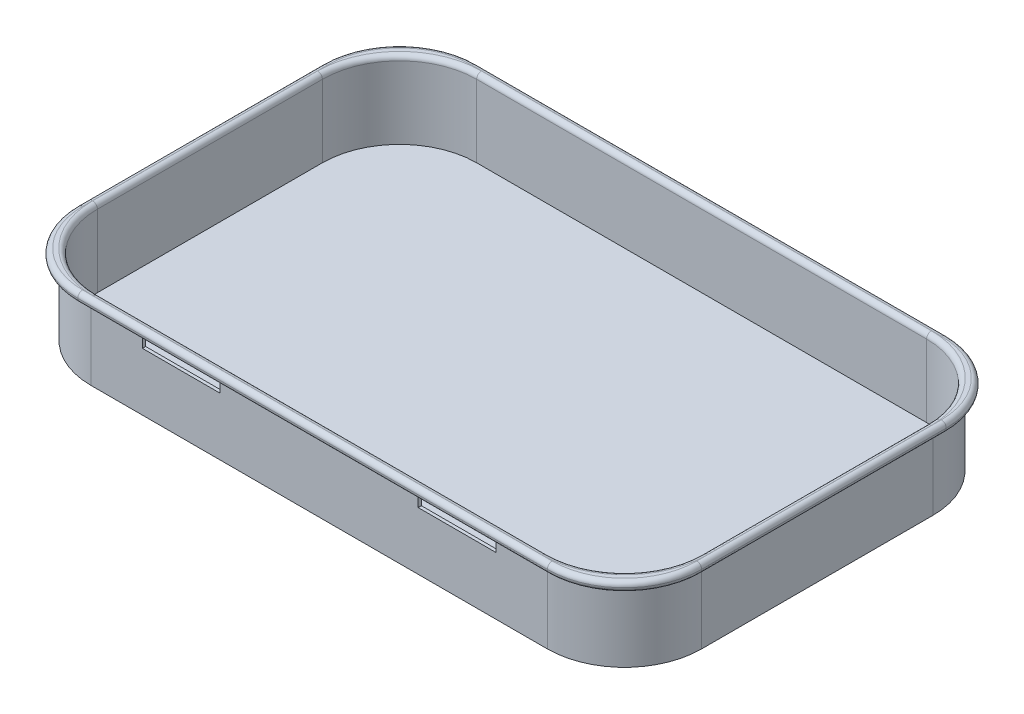
SolidWorks part; units mm, degrees
material "AISI 1010 Steel, hot rolled bar"
ref_plane "Front Plane" through (0, 0, 0) normal (0, 0, 1) x (1, 0, 0)
ref_plane "Top Plane" through (0, 0, 0) normal (0, 1, 0) x (1, 0, 0)
ref_plane "Right Plane" through (0, 0, 0) normal (1, 0, 0) x (0, 0, -1)
sketch "Sketch1" plane through (0, 0, 0) normal (0, 1, 0) x (1, 0, 0)
  line L0 (-47.5, 30) -> (47.5, -30) construction
  line L1 (-47.5, -30) -> (47.5, -30)
  line L2 (-47.5, -30) -> (-47.5, 30)
  line L3 (-47.5, 30) -> (47.5, 30)
  line L4 (47.5, -30) -> (47.5, 30)
  point P5 (0, 0)
  dimension "D1" = 95
  dimension "D2" = 60
extrude "Boss-Extrude1" add sketch "Sketch1" along normal blind 0.5
sketch "Sketch2" plane through (0, 0.5, 0) normal (0, 1, 0) x (1, 0, 0)
  line L0 (-47, -29.5) -> (47, -29.5)
  line L1 (47, -29.5) -> (47, 29.5)
  line L2 (47, 29.5) -> (-47, 29.5)
  line L3 (-47, 29.5) -> (-47, -29.5)
  line L8 (-47.5, -30) -> (47.5, -30)
  line L9 (47.5, -30) -> (47.5, 30)
  line L10 (47.5, 30) -> (-47.5, 30)
  line L11 (-47.5, 30) -> (-47.5, -30)
  line L12 (-47.5, -30) -> (47.5, -30)
  line L13 (47.5, -30) -> (47.5, 30)
  line L14 (47.5, 30) -> (-47.5, 30)
  line L15 (-47.5, 30) -> (-47.5, -30)
  line M9 (-47.5, 30) -> (-47.5, -30)
  line M10 (-47.5, -30) -> (47.5, -30)
  line M11 (47.5, -30) -> (47.5, 30)
  line M12 (47.5, 30) -> (-47.5, 30)
  dimension "D1" = 0
  dimension "D2" = 0.5
extrude "Boss-Extrude2" add sketch "Sketch2" along normal blind 10.5 contours L3 L2 L1 L0 M12 M9 M10 M11
sketch "Sketch3" plane through (0, 11, 0) normal (0, 1, 0) x (1, 0, 0)
  line L8 (-48.53, -31.03) -> (48.53, -31.03)
  line L9 (48.53, -31.03) -> (48.53, 31.03)
  line L10 (48.53, 31.03) -> (-48.53, 31.03)
  line L11 (-48.53, 31.03) -> (-48.53, -31.03)
  line L12 (-48.53, -31.03) -> (48.53, -31.03)
  line L13 (48.53, -31.03) -> (48.53, 31.03)
  line L14 (48.53, 31.03) -> (-48.53, 31.03)
  line L15 (-48.53, 31.03) -> (-48.53, -31.03)
  line L20 (47, -29.5) -> (47, 29.5)
  line L21 (-47, -29.5) -> (47, -29.5)
  line L22 (47, 29.5) -> (-47, 29.5)
  line L23 (-47, 29.5) -> (-47, -29.5)
  line L24 (47, -29.5) -> (47, 29.5)
  line L25 (-47, -29.5) -> (47, -29.5)
  line L26 (47, 29.5) -> (-47, 29.5)
  line L27 (-47, 29.5) -> (-47, -29.5)
  dimension "D1" = 1.53
  dimension "D2" = 0
extrude "Boss-Extrude3" add sketch "Sketch3" along normal blind 1.5
fillet "Fillet2" radius 12 4 edges at (47, 6.5, -29.5) (47, 6.5, 29.5) (-47, 6.5, 29.5) (-47.5, 5.5, -30)
fillet "Fillet3" radius 12 8 edges at (-47.5, 5.5, 30) (-48.53, 11.75, 31.03) (-48.53, 11.75, -31.03) (-47, 6.5, -29.5) (47.5, 5.5, -30) (48.53, 11.75, -31.03) (47.5, 5.5, 30) (48.53, 11.75, 31.03)
fillet "Fillet4" radius 0.749 24 edges at (43.4853, 12.5, 25.9853) (0, 12.5, 29.5) (-43.4853, 12.5, 25.9853) (-47, 12.5, 0) (-43.4853, 12.5, -25.9853) (0, 12.5, -29.5) (43.4853, 12.5, -25.9853) (45.0153, 12.5, -27.5153) (48.53, 12.5, 0) (45.0153, 12.5, 27.5153) (0, 12.5, 31.03) (-45.0153, 12.5, 27.5153) (-48.53, 12.5, 0) (-45.0153, 12.5, -27.5153) (45.0153, 11, -27.5153) (48.53, 11, 0) (45.0153, 11, 27.5153) (0, 11, 31.03) (-45.0153, 11, 27.5153) (-48.53, 11, 0) (-45.0153, 11, -27.5153) (47, 12.5, 0) (0, 12.5, -31.03) (0, 11, -31.03)
sketch "Sketch4" plane through (0, 0, 29.5) normal (0, 0, -1) x (-1, 0, 0)
  line L0 (36.53, 12.5) -> (-36.53, 12.5) construction
  line L1 (-27.5, 10.5) -> (-15.4, 10.5)
  line L2 (-27.5, 10.5) -> (-27.5, 9)
  line L3 (-27.5, 9) -> (-15.4, 9)
  line L4 (-15.4, 10.5) -> (-15.4, 9)
  line L5 (15.4, 10.5) -> (27.5, 10.5)
  line L6 (15.4, 10.5) -> (15.4, 9)
  line L7 (15.4, 9) -> (27.5, 9)
  line L8 (27.5, 10.5) -> (27.5, 9)
  line L10 (35.5, 11) -> (35.5, 0) construction
  line L11 (-35.5, 0) -> (-35.5, 11) construction
  dimension "D1" = 12.1
  dimension "D2" = 1.5
  dimension "D3" = 2
  dimension "D4" = 8
  dimension "D5" = 8
extrude "Cut-Extrude1" cut sketch "Sketch4" against normal up to surface (0.5 mm away) up to face at (0, 5.5, 30)
